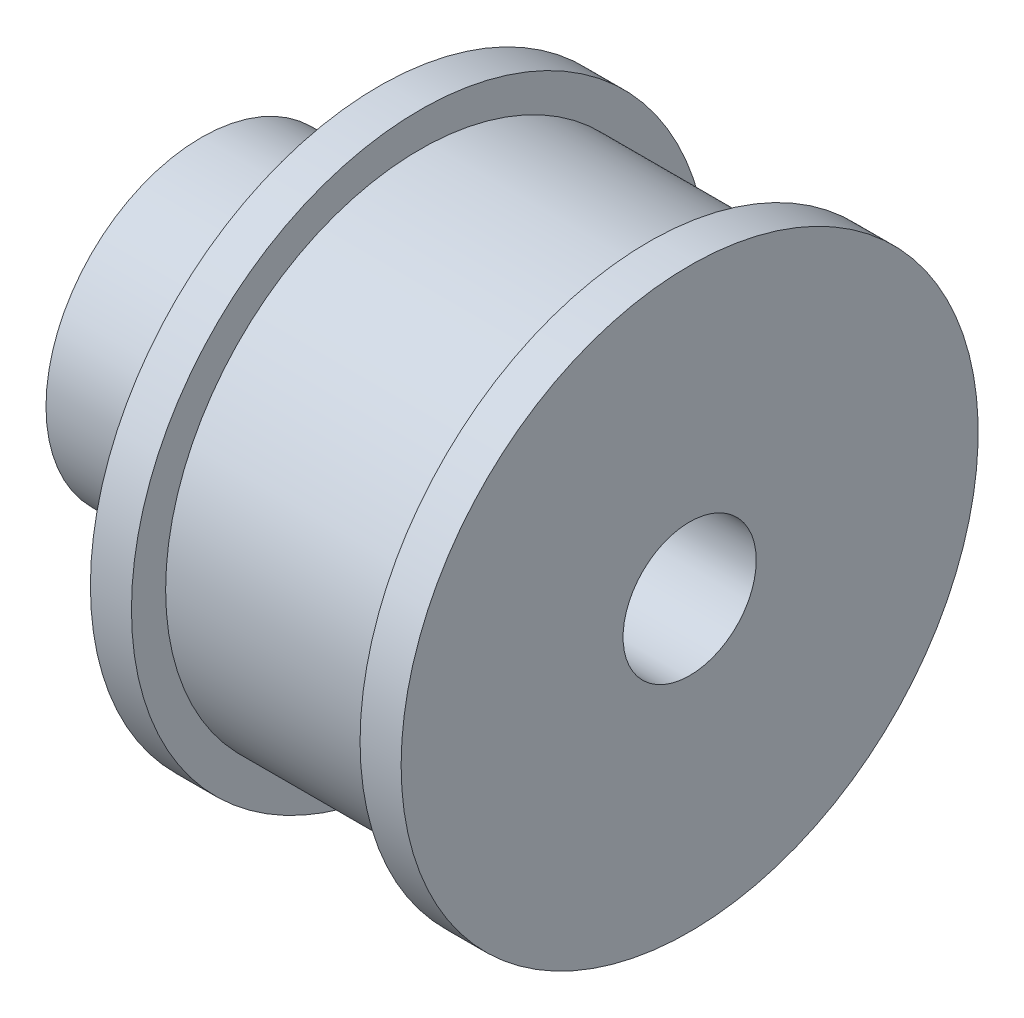
SolidWorks part; units mm, degrees
ref_plane "Front Plane" through (0, 0, 0) normal (0, 0, 1) x (1, 0, 0)
ref_plane "Top Plane" through (0, 0, 0) normal (0, 1, 0) x (1, 0, 0)
ref_plane "Right Plane" through (0, 0, 0) normal (1, 0, 0) x (0, 0, -1)
sketch "Sketch1" plane through (0, 0, 0) normal (0, 1, 0) x (1, 0, 0)
  line L0 (0, -11.46) -> (-5.15, -11.46)
  line L1 (-5.15, -13) -> (-7, -13)
  line L2 (-7, -13) -> (-7, -7)
  line L3 (7, 0) -> (7, -13)
  line L4 (7, -13) -> (5.15, -13)
  line L5 (5.15, -13) -> (5.15, -11.46)
  line L6 (5.15, -11.46) -> (0, -11.46)
  line L7 (-5.15, -11.46) -> (-5.15, -13)
  line L8 (-7, 0) -> (7, 0) construction
  line L9 (7, 0) -> (-7, 0)
  line L10 (-15, 0) -> (-15, -7)
  line L11 (-15, -7) -> (-7, -7)
  line L12 (-15, 0) -> (-7, 0)
  dimension "D1" = 13
  dimension "D2" = 1.85
  dimension "D3" = 7
  dimension "D4" = 11.46
  dimension "D5" = 7
  dimension "D6" = 1.85
  dimension "D7" = 7
  dimension "D8" = 8
revolve "Revolve1" add sketch "Sketch1" angle 360 about L8
hole_wizard "Ø6.0 (6) Diameter Hole2" positions "Sketch8" profile "Sketch7" hole size "Ø6.0" standard "ANSI Metric"
sketch "Sketch8" plane through (7, 0, 0) normal (1, 0, 0) x (0, 0, -1)
  point P0 (0, 0)
sketch "Sketch7" plane through (7, 0, 0) normal (0, 1, 0) x (0, 0, -1)
  line L0 (0, 0) -> (0, 25.8026)
  line L1 (0, 25.8026) -> (3, 24)
  line L2 (3, 24) -> (3, 0)
  line L5 (3, 0) -> (0, 0)
  line L10 (0, 25.8026) -> (-3, 24) construction
  line L11 (0, -6.35) -> (0, 107.95) construction
  dimension "Hole Dia." = 6
  dimension "Hole Depth" = 24
  dimension "Drill Angle" = 118
